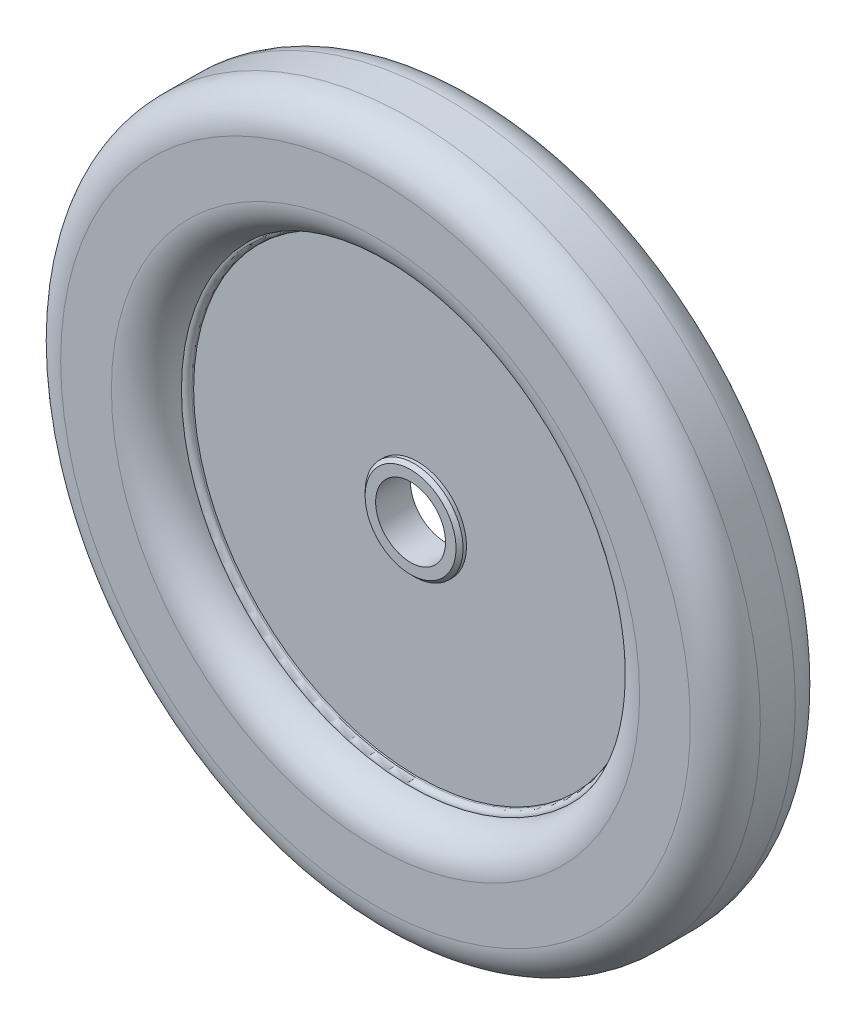
SolidWorks part; units mm, degrees
ref_plane "Front Plane" through (0, 0, 0) normal (0, 0, 1) x (1, 0, 0)
ref_plane "Top Plane" through (0, 0, 0) normal (0, 1, 0) x (1, 0, 0)
ref_plane "Right Plane" through (0, 0, 0) normal (1, 0, 0) x (0, 0, -1)
sketch "Sketch3" plane through (0, 0, 0) normal (0, 1, 0) x (1, 0, 0)
  line L0 (10, 0) -> (13, 0)
  line L2 (13, 9.9586) -> (10, 9.9586)
  line L3 (0, 9.9586) -> (0, 0) construction
  line L4 (64, 8.4586) -> (64, 7.9793)
  line L5 (10, 9.9586) -> (10, 0)
  line L6 (14, 1.9793) -> (64, 1.9793)
  line L7 (14, 7.9793) -> (64, 7.9793)
  line L8 (64, 1.9793) -> (64, 1.5)
  line L12 (14, 1.9793) -> (14, 1)
  line L13 (13, 9.9586) -> (14, 8.9586)
  line L14 (14, 1) -> (13, 0)
  line L15 (14, 7.9793) -> (14, 8.9586)
  line L16 (65.5, 9.9586) -> (65.5, 9.9793)
  line L17 (75.5, 19.9793) -> (90, 19.9793)
  line L18 (100, 9.9793) -> (100, -0.0207)
  line L19 (75.5, -10.0207) -> (90, -10.0207)
  line L20 (65.5, -0.0207) -> (65.5, 0)
  arc A1 (64, 8.4586) -> (65.5, 9.9586) centre (65.5, 8.4586) cw
  arc A2 (64, 1.5) -> (65.5, 0) centre (65.5, 1.5) ccw
  arc A3 (65.5, 9.9793) -> (75.5, 19.9793) centre (75.5, 9.9793) cw
  arc A4 (100, 9.9793) -> (90, 19.9793) centre (90, 9.9793) ccw
  arc A5 (100, -0.0207) -> (90, -10.0207) centre (90, -0.0207) cw
  arc A6 (65.5, -0.0207) -> (75.5, -10.0207) centre (75.5, -0.0207) ccw
  point P16 (14, 9.9586)
  point P18 (14, 0)
  dimension "D3" = 10
  dimension "D1" = 1.5
  dimension "D2" = 1.5
  dimension "D11" = 10
  dimension "D12" = 10
  dimension "D6" = 50
revolve "Revolve1" add sketch "Sketch3" angle 360 about L3
